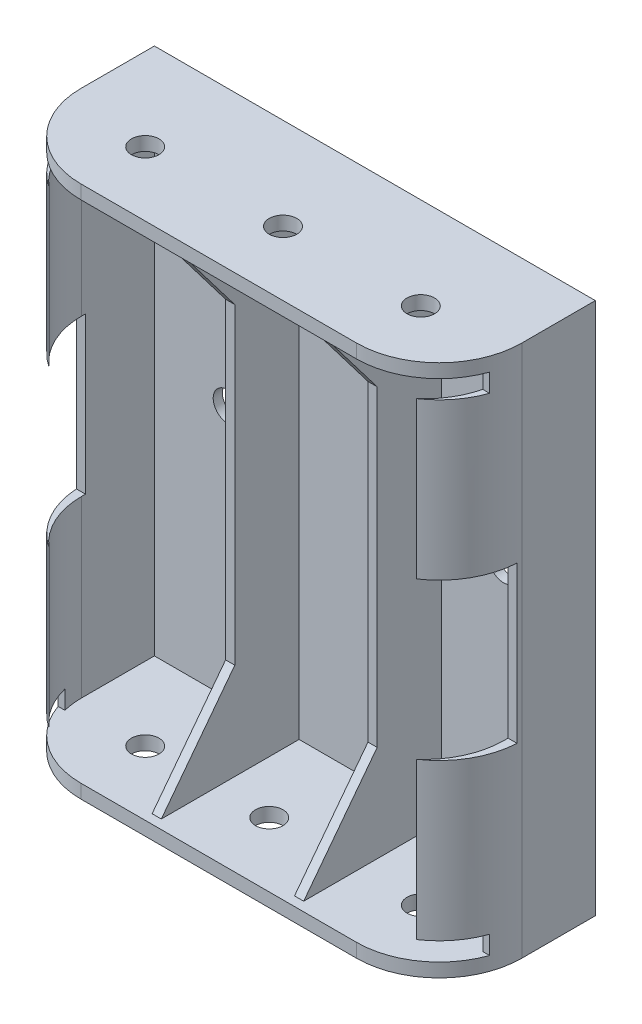
SolidWorks part; units mm, degrees
ref_plane "Front Plane" through (0, 0, 0) normal (0, 0, 1) x (1, 0, 0)
ref_plane "Top Plane" through (0, 0, 0) normal (0, 1, 0) x (1, 0, 0)
ref_plane "Right Plane" through (0, 0, 0) normal (1, 0, 0) x (0, 0, -1)
sketch "Sketch2" plane through (0, 0, 0) normal (0, 1, 0) x (1, 0, 0)
  line L0 (24, 0) -> (-24, 0)
  line L1 (-24, 0) -> (-24, -8)
  line L2 (15, -17) -> (-15, -17)
  line L3 (0, -17) -> (0, 0) construction
  line L4 (24, 0) -> (24, -8)
  arc A0 (-24, -8) -> (-15, -17) centre (-15, -8) ccw
  arc A1 (24, -8) -> (15, -17) centre (15, -8) cw
  point P8 (-17.5901, -30.6335)
  dimension "D3" = 9
  dimension "D1" = 24
  dimension "D2" = 17
extrude "Boss-Extrude1" add sketch "Sketch2" along normal mid plane 58
sketch "Sketch3" plane through (0, -29, 0) normal (0, -1, 0) x (1, 0, 0)
  line L0 (24, 0) -> (-24, 0) construction
  line L1 (-14.3196, 17.6) -> (14.3196, 17.6)
  line L2 (-23, 8.9196) -> (-23, 1)
  line L3 (-23, 1) -> (23, 1)
  line L4 (23, 8.9196) -> (23, 1)
  line L5 (24, 8) -> (24, 0) construction
  line L6 (-24, 0) -> (-24, 8) construction
  arc A0 (14.3196, 17.6) -> (23, 8.9196) centre (14.3196, 8.9196) cw
  arc A1 (-14.3196, 17.6) -> (-23, 8.9196) centre (-14.3196, 8.9196) ccw
  arc A2 (24, 8) -> (15, 17) centre (15, 8) ccw construction
  point P14 (20, 15.4833)
  point P15 (0, 0)
  dimension "D5" = 4
  dimension "D1" = 1
  dimension "D2" = 1
  dimension "D3" = 1
  dimension "D4" = 16.6
extrude "Cut-Extrude1" cut sketch "Sketch3" against normal offset from surface (55 mm away) 1.5 from offset 1.5 up to face at (0, 29, 8.9547) offset against normal yes
ref_plane "Plane1" through (7.75, 0, 0) normal (1, 0, 0) x (0, 0, -1)
sketch "Sketch4" plane through (7.75, 0, 0) normal (1, 0, 0) x (0, 0, -1)
  line L0 (-16, 27.5) -> (-1, 27.5)
  line L1 (-15.4833, 27.5) -> (-8.9196, 27.5) construction
  line L2 (-1, 27.5) -> (-1, -27.5)
  line L3 (-1, 27.5) -> (-1, -27.5) construction
  line L4 (-1, 0) -> (-8, 0) construction
  line L5 (-8, -17) -> (-8, 17)
  line L6 (-8, 17) -> (-16, 27.5)
  line L7 (0, 29) -> (0, -29) construction
  line L8 (-17, 29) -> (-17, 27.5) construction
  line L9 (-8, 29) -> (-17, 29) construction
  line L10 (-16, -27.5) -> (-1, -27.5)
  line L11 (-8, -17) -> (-16, -27.5)
  dimension "D1" = 8
  dimension "D2" = 1
  dimension "D3" = 12
extrude "Boss-Extrude2" add sketch "Sketch4" along normal mid plane 1
mirror "Mirror1" about plane through (0, 0, 0) normal (1, 0, 0) of "Boss-Extrude2"
sketch "Sketch5" plane through (0, 0, 0) normal (1, 0, 0) x (0, 0, -1)
  line L5 (-17, 8.5) -> (-8.5, 8.5)
  line L6 (-17, 8.5) -> (-17, -8.5)
  line L7 (-17, -8.5) -> (-8.5, -8.5)
  line L8 (-8.5, 8.5) -> (-8.5, -8.5)
  line L14 (0, 29) -> (0, -29) construction
  line L15 (0, 0) -> (-8.5, 0) construction
  line L20 (-17, 29) -> (-17, 27.5) construction
  dimension "D2" = 8.5
  dimension "D4" = 17
extrude "Cut-Extrude2" cut sketch "Sketch5" against normal through all both and the other way through all
sketch "Sketch6" plane through (24, 0, 0) normal (1, 0, 0) x (0, 0, -1)
  line L0 (0, 0) -> (-15.1239, 0) construction
  line L1 (-17, 27.5) -> (-11, 27.5)
  line L2 (-17, 27.5) -> (-17, 25.5)
  line L3 (-17, 25.5) -> (-11, 25.5)
  line L4 (-11, 27.5) -> (-11, 25.5)
  line L5 (-11, -27.5) -> (-11, -25.5)
  line L6 (-17, -25.5) -> (-11, -25.5)
  line L7 (-17, -27.5) -> (-17, -25.5)
  line L8 (-17, -27.5) -> (-11, -27.5)
  dimension "D1" = 2
  dimension "D2" = 6
extrude "Cut-Extrude3" cut sketch "Sketch6" against normal blind 10
mirror "Mirror2" about plane through (0, 0, 0) normal (1, 0, 0) of "Cut-Extrude3"
sketch "Sketch7" plane through (0, 29, 0) normal (0, 1, 0) x (1, 0, 0)
  line L0 (-15, -10) -> (0, -10) construction
  line L1 (0, -10) -> (15, -10) construction
  line L2 (24, 0) -> (-24, 0) construction
  line L3 (0, 0) -> (0, -10) construction
  circle A0 centre (-15, -10) radius 1.5
  circle A1 centre (0, -10) radius 1.5
  circle A2 centre (15, -10) radius 1.5
  dimension "D3" = 3
  dimension "D1" = 10
  dimension "D2" = 15
extrude "Cut-Extrude4" cut sketch "Sketch7" against normal blind 10
sketch "Sketch8" plane through (0, -29, 0) normal (0, -1, 0) x (1, 0, 0)
  line L0 (-15, 10) -> (-1.5, 10) construction
  circle A0 centre (-15, 10) radius 1.5
  circle A1 centre (15, 10) radius 1.5
  circle A2 centre (-1.5, 10) radius 1.5
  circle A3 centre (-15, 10) radius 1.5 construction
  circle A4 centre (15, 10) radius 1.5 construction
  dimension "D1" = 13.5
extrude "Cut-Extrude5" cut sketch "Sketch8" against normal blind 10
sketch "Sketch9" plane through (0, 0, 0) normal (0, 0, -1) x (-1, 0, 0)
  line L0 (-15, 0) -> (0, 0) construction
  line L1 (0, 0) -> (0, -29) construction
  line L2 (-24, -29) -> (24, -29) construction
  circle A0 centre (-15, 0) radius 1.6
  circle A1 centre (15, 0) radius 1.6
  dimension "D2" = 3.2
  dimension "D1" = 15
extrude "Cut-Extrude6" cut sketch "Sketch9" against normal through all
